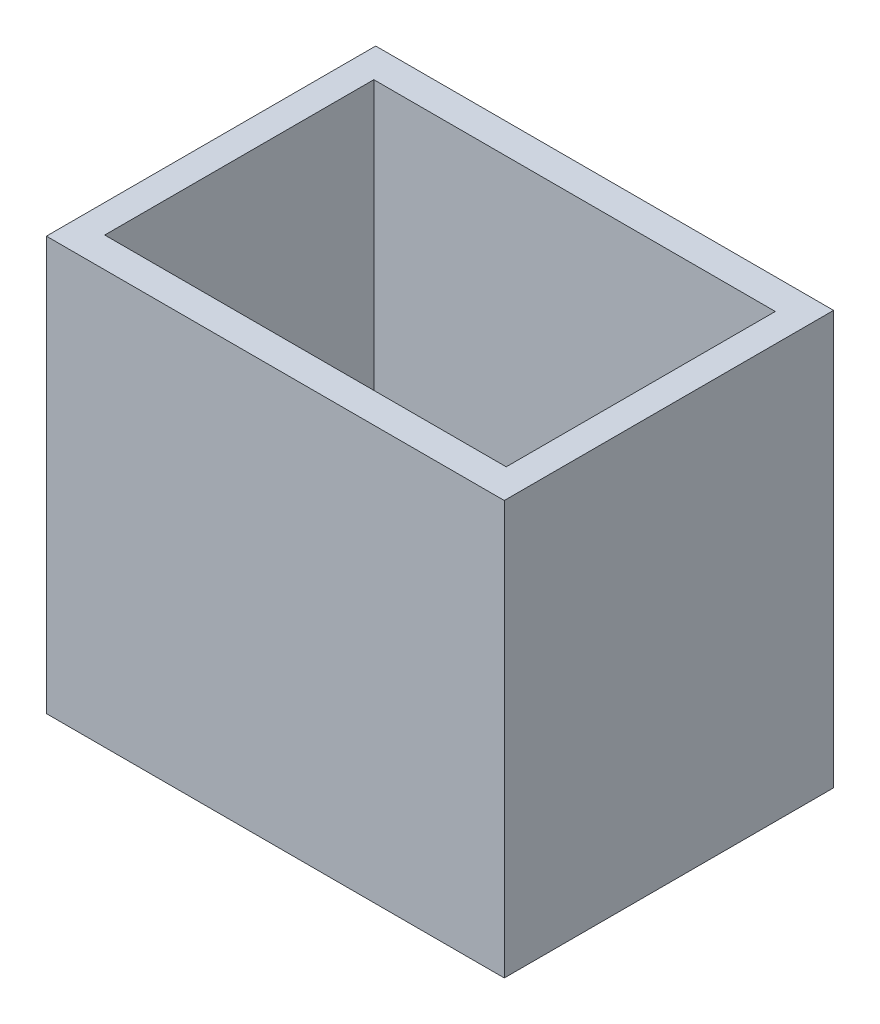
SolidWorks part; units mm, degrees
ref_plane "Front Plane" through (0, 0, 0) normal (0, 0, 1) x (1, 0, 0)
ref_plane "Top Plane" through (0, 0, 0) normal (0, 1, 0) x (1, 0, 0)
ref_plane "Right Plane" through (0, 0, 0) normal (1, 0, 0) x (0, 0, -1)
sketch "Sketch1" plane through (0, 0, 0) normal (0, 1, 0) x (1, 0, 0)
  line L0 (-32.1911, -1.2047) -> (-32.1911, -18.7247)
  line L1 (-32.1911, -18.7247) -> (-7.8311, -18.7247)
  line L2 (-7.8311, -18.7247) -> (-7.8311, -1.2047)
  line L3 (-7.8311, -1.2047) -> (-32.1911, -1.2047)
extrude "Boss-Extrude1" add sketch "Sketch1" along normal blind 22 contours L3 L0 L1 L2
sketch "Sketch2" plane through (0, 22, 0) normal (0, 1, 0) x (1, 0, 0)
  line L6 (-30.6902, -2.8063) -> (-30.6902, -17.1221)
  line L9 (-30.6902, -2.8063) -> (-9.3311, -2.8063)
  line L10 (-9.3311, -2.8063) -> (-9.3311, -17.1221)
  line L11 (-9.3311, -17.1221) -> (-30.6902, -17.1221)
  point P0 (0, 0)
extrude "Cut-Extrude1" cut sketch "Sketch2" against normal blind 21 contours L11 L10 L9 L6
